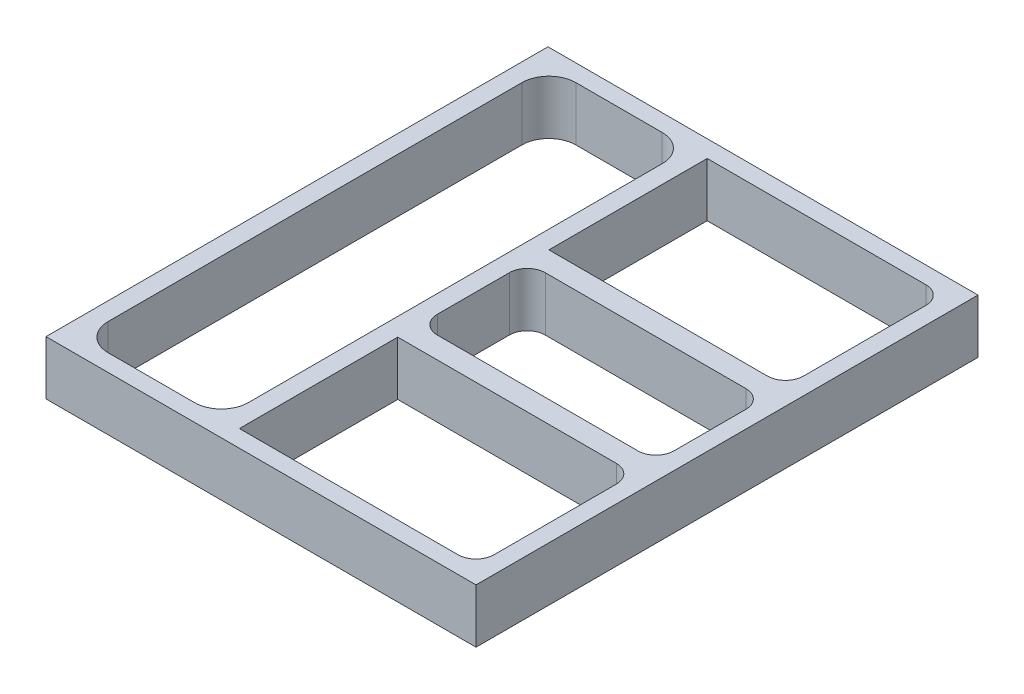
SolidWorks part; units mm, degrees
ref_plane "Front Plane" through (0, 0, 0) normal (0, 0, 1) x (1, 0, 0)
ref_plane "Top Plane" through (0, 0, 0) normal (0, 1, 0) x (1, 0, 0)
ref_plane "Right Plane" through (0, 0, 0) normal (1, 0, 0) x (0, 0, -1)
sketch "Sketch1" plane through (0, -0.635, 0) normal (0, -1, 0) x (-1, 0, 0)
  line L4 (13.6525, 26.67) -> (13.6525, 82.55) construction
  line L5 (13.6525, 82.55) -> (-63.5, 82.55) construction
  line L6 (-69.85, 76.2) -> (-69.85, 33.02) construction
  line L7 (-63.5, 26.67) -> (13.6525, 26.67) construction
  line L8 (-75.8825, 88.5825) -> (-75.8825, -88.5825)
  line L9 (-75.8825, -88.5825) -> (75.8825, -88.5825)
  line L10 (75.8825, -88.5825) -> (75.8825, 88.5825)
  line L11 (75.8825, 88.5825) -> (-75.8825, 88.5825)
  line L12 (-75.8825, 88.5825) -> (-75.8825, -88.5825)
  line L13 (-75.8825, -88.5825) -> (75.8825, -88.5825)
  line L14 (75.8825, -88.5825) -> (75.8825, 88.5825)
  line L15 (75.8825, 88.5825) -> (-75.8825, 88.5825)
  line L16 (13.6525, -82.55) -> (13.6525, -26.67) construction
  line L17 (13.6525, -26.67) -> (-63.5, -26.67) construction
  line L18 (-69.85, -33.02) -> (-69.85, -76.2) construction
  line L19 (-63.5, -82.55) -> (13.6525, -82.55) construction
  line L20 (13.6525, 26.67) -> (13.6525, 82.55)
  line L21 (13.6525, 82.55) -> (-63.5, 82.55)
  line L22 (-69.85, 76.2) -> (-69.85, 33.02)
  line L23 (-63.5, 26.67) -> (13.6525, 26.67)
  line L24 (13.6525, -82.55) -> (13.6525, -26.67)
  line L25 (13.6525, -26.67) -> (-63.5, -26.67)
  line L26 (-69.85, -33.02) -> (-69.85, -76.2)
  line L27 (-63.5, -82.55) -> (13.6525, -82.55)
  line L29 (7.3025, -19.05) -> (-63.5, -19.05)
  line L30 (13.6525, -12.7) -> (13.6525, 12.7)
  line L31 (7.3025, 19.05) -> (-63.5, 19.05)
  line L32 (-69.85, -12.7) -> (-69.85, 12.7)
  line L33 (29.5275, -82.55) -> (60.0075, -82.55)
  line L34 (20.0025, -73.025) -> (20.0025, 73.025)
  line L35 (29.5275, 82.55) -> (60.0075, 82.55)
  line L36 (69.5325, -73.025) -> (69.5325, 73.025)
  arc A2 (-63.5, 82.55) -> (-69.85, 76.2) centre (-63.5, 76.2) ccw construction
  arc A3 (-69.85, 33.02) -> (-63.5, 26.67) centre (-63.5, 33.02) ccw construction
  arc A4 (-63.5, -26.67) -> (-69.85, -33.02) centre (-63.5, -33.02) ccw construction
  arc A5 (-69.85, -76.2) -> (-63.5, -82.55) centre (-63.5, -76.2) ccw construction
  arc A6 (-63.5, 82.55) -> (-69.85, 76.2) centre (-63.5, 76.2) ccw
  arc A7 (-69.85, 33.02) -> (-63.5, 26.67) centre (-63.5, 33.02) ccw
  arc A8 (-63.5, -26.67) -> (-69.85, -33.02) centre (-63.5, -33.02) ccw
  arc A9 (-69.85, -76.2) -> (-63.5, -82.55) centre (-63.5, -76.2) ccw
  arc A10 (13.6525, 12.7) -> (7.3025, 19.05) centre (7.3025, 12.7) ccw
  arc A11 (7.3025, -19.05) -> (13.6525, -12.7) centre (7.3025, -12.7) ccw
  arc A12 (-63.5, 19.05) -> (-69.85, 12.7) centre (-63.5, 12.7) ccw
  arc A13 (-63.5, -19.05) -> (-69.85, -12.7) centre (-63.5, -12.7) cw
  arc A14 (20.0025, 73.025) -> (29.5275, 82.55) centre (29.5275, 73.025) cw
  arc A15 (60.0075, 82.55) -> (69.5325, 73.025) centre (60.0075, 73.025) cw
  arc A16 (60.0075, -82.55) -> (69.5325, -73.025) centre (60.0075, -73.025) ccw
  arc A17 (29.5275, -82.55) -> (20.0025, -73.025) centre (29.5275, -73.025) cw
  point P25 (-75.8825, 0)
  point P28 (-69.85, 0)
  point P30 (0, 0)
  dimension "D5" = 6.35
  dimension "D6" = 9.525
  dimension "D2" = 38.1
  dimension "D3" = 6.35
  dimension "D4" = 6.35
  dimension "D1" = 0.3175
extrude "Boss-Extrude1" add sketch "Sketch1" along normal blind 19.05 contours L13 L14 L15 L12
